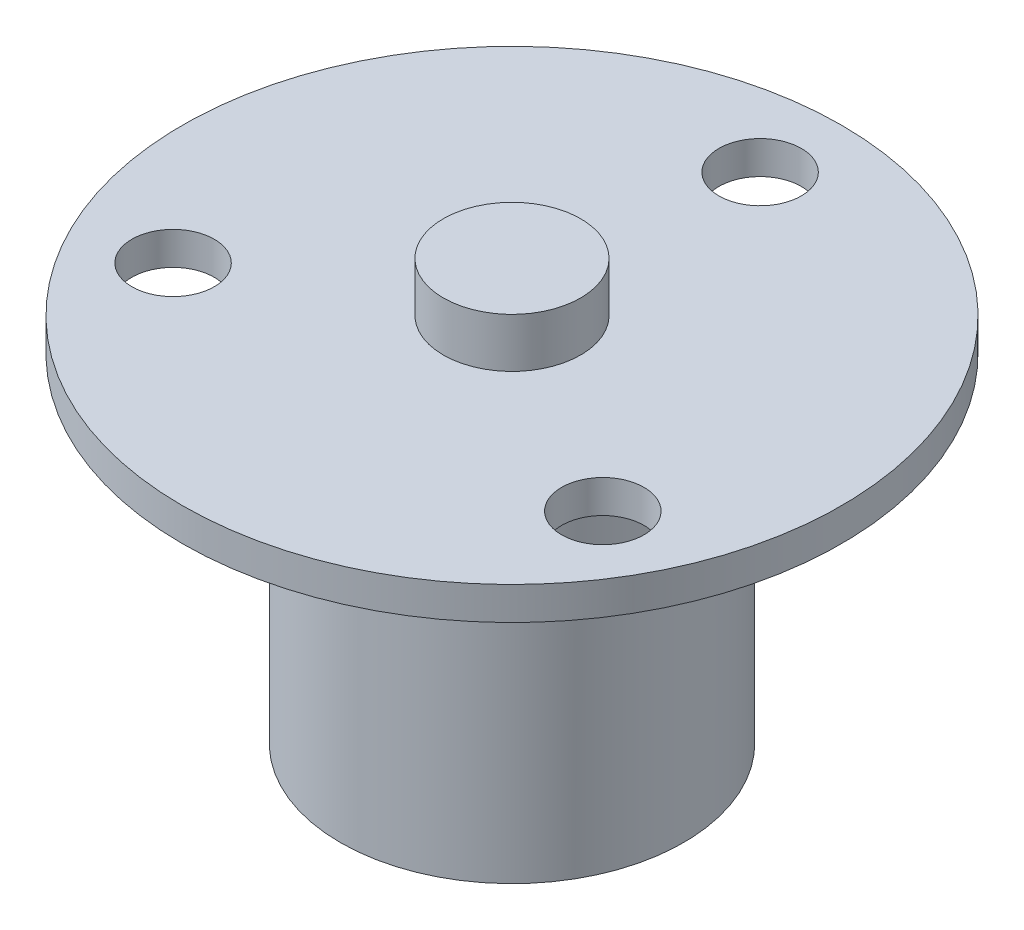
SolidWorks part; units mm, degrees
ref_plane "Front Plane" through (0, 0, 0) normal (0, 0, 1) x (1, 0, 0)
ref_plane "Top Plane" through (0, 0, 0) normal (0, 1, 0) x (1, 0, 0)
ref_plane "Right Plane" through (0, 0, 0) normal (1, 0, 0) x (0, 0, -1)
sketch "Sketch1" plane through (0, 0, 0) normal (0, 1, 0) x (1, 0, 0)
  circle A0 centre (0, 0) radius 12
  circle A1 centre (0, 0) radius 2.5
  dimension "D1" = 24
  dimension "D2" = 5
extrude "Boss-Extrude1" add sketch "Sketch1" along normal blind 1.2
sketch "Sketch2" plane through (0, 1.2, 0) normal (0, 1, 0) x (1, 0, 0)
  line L0 (0, 9.0345) -> (0, 0)
  line L1 (0, 0) -> (7.8241, -4.5172)
  line L2 (7.8241, -4.5172) -> (0, 0)
  line L3 (0, 0) -> (-7.8241, -4.5172)
  circle A0 centre (0, 0) radius 9.0345
  circle A1 centre (0, 9.0345) radius 1.5
  circle A2 centre (7.8241, -4.5172) radius 1.5
  circle A3 centre (-7.8241, -4.5172) radius 1.5
  dimension "D3" = 3
  dimension "D4" = 3
  dimension "D5" = 3
  dimension "D6" = 18.0689
  dimension "D1" = 120
  dimension "D2" = 120
extrude "Cut-Extrude1" cut sketch "Sketch2" against normal blind 1.2 contours A0 A1 L0 | L0 A1 A0 | A0 A1 | A0 A2 | A0 A2 L2 | L2 A2 A0 | A0 A3 L3 | L3 A3 A0 | A0 A3
sketch "Sketch3" plane through (0, 0, 0) normal (0, -1, 0) x (-1, 0, 0)
  circle A0 centre (0, 0) radius 6.25
  dimension "D1" = 12.5
extrude "Boss-Extrude2" add sketch "Sketch3" along normal blind 12.3
sketch "Sketch4" plane through (0, 0, 0) normal (0, 1, 0) x (1, 0, 0)
  circle A0 centre (0, 0) radius 2.5
extrude "Boss-Extrude3" add sketch "Sketch4" along normal blind 3
